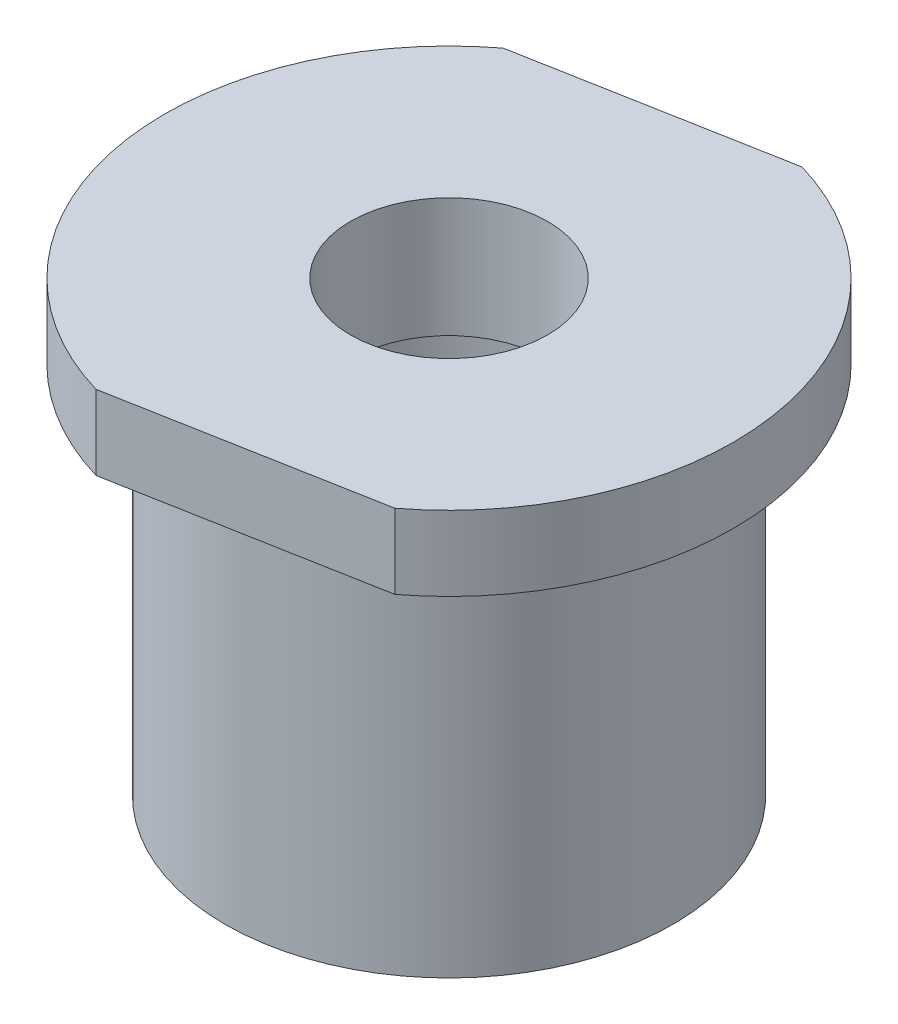
SolidWorks part; units mm, degrees
material "Polyetheretherketone (PEEK)"
ref_plane "Front Plane" through (0, 0, 0) normal (0, 0, 1) x (1, 0, 0)
ref_plane "Top Plane" through (0, 0, 0) normal (0, 1, 0) x (1, 0, 0)
ref_plane "Right Plane" through (0, 0, 0) normal (1, 0, 0) x (0, 0, -1)
sketch "Sketch1" plane through (0, 0, 0) normal (0, 0, 1) x (1, 0, 0)
  line L0 (0, 7.5) -> (0, -7.5) construction
  line L1 (0, 7.5) -> (-9.525, 7.5)
  line L2 (-9.525, 7.5) -> (-9.525, 5)
  line L3 (-9.525, 5) -> (-7.5, 5)
  line L4 (-7.5, 5) -> (-7.5, -7.5)
  line L5 (-7.5, -7.5) -> (0, -7.5)
  line L6 (0, 7.5) -> (0, -7.5)
  dimension "D1" = 2.5
  dimension "D2" = 19.05
  dimension "D3" = 15
  dimension "D4" = 15
revolve "Revolve1" add sketch "Sketch1" angle 360 about L0
sketch "Sketch2" plane through (0, 7.5, 0) normal (0, 1, 0) x (1, 0, 0)
  circle A0 centre (0, 0) radius 3.3
  dimension "D1" = 6.6
extrude "Cut-Extrude1" cut sketch "Sketch2" against normal through all
sketch "Sketch3" plane through (0, -7.5, 0) normal (0, -1, 0) x (1, 0, 0)
  circle A0 centre (0, 0) radius 5
  dimension "D1" = 10
extrude "Cut-Extrude2" cut sketch "Sketch3" against normal blind 11
sketch "Sketch4" plane through (0, 7.5, 0) normal (0, 1, 0) x (1, 0, 0)
  line L0 (2.6868, 9.1382) -> (-5.7675, 7.5803)
  line L1 (5.7675, -7.5803) -> (-2.6868, -9.1382)
  circle A0 centre (0, 0) radius 9.525 construction
  circle A1 centre (0, 0) radius 3.3 construction
  arc A2 (-2.6868, -9.1382) -> (5.7675, -7.5803) centre (0, 0) ccw
  arc A3 (2.6868, 9.1382) -> (-5.7675, 7.5803) centre (0, 0) ccw
  dimension "D1" = 17
  dimension "D2" = 8.5
extrude "Cut-Extrude3" cut sketch "Sketch4" against normal through all
